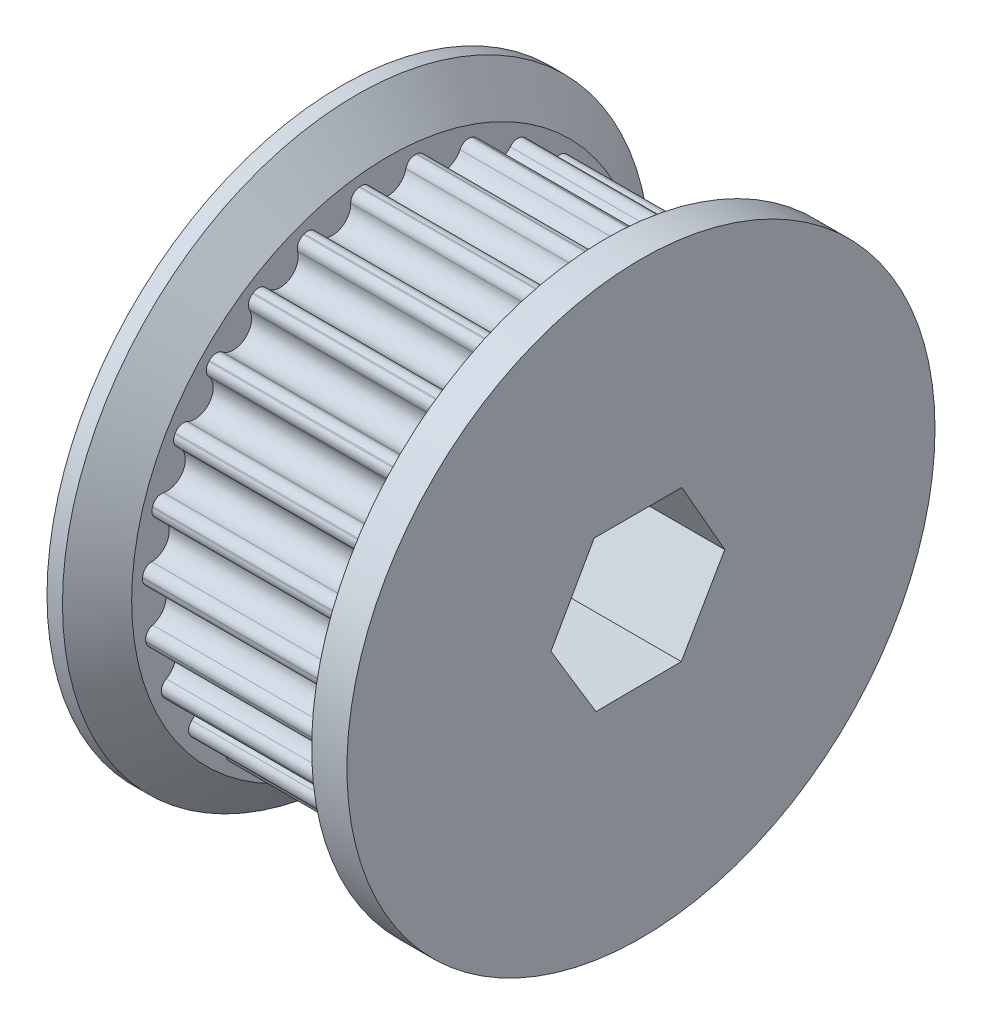
SolidWorks part; units mm, degrees
ref_plane "Front Plane" through (0, 0, 0) normal (0, 0, 1) x (1, 0, 0)
ref_plane "Top Plane" through (0, 0, 0) normal (0, 1, 0) x (1, 0, 0)
ref_plane "Right Plane" through (0, 0, 0) normal (1, 0, 0) x (0, 0, -1)
sketch "Sketch1" plane through (0, 0, 0) normal (1, 0, 0) x (0, 0, -1)
  circle A0 centre (0, 0) radius 20.915
  dimension "D1" = 41.83
extrude "Boss-Extrude1" add sketch "Sketch1" along normal blind 18.5 contours A0
sketch "Sketch8" plane through (18.5, 0, 0) normal (1, 0, 0) x (0, 0, -1)
  line L1 (0, 0) -> (0, 50.3807) construction
  line L7 (-2.5, 21.3391) -> (0, 0) construction
  line L8 (0, 0) -> (2.5, 21.3391) construction
  circle A0 centre (0, 0) radius 21.485 construction
  circle A2 centre (0, 0) radius 20.915 construction
  arc A3 (-1.4883, 20.862) -> (1.4883, 20.862) centre (0, 20.4573) ccw
  arc A6 (-1.4883, 20.862) -> (1.4883, 20.862) centre (0, 0) cw
  point P15 (0, 18.915)
  point P16 (0, 20.915)
  dimension "D4" = 1.5423
  dimension "D2" = 42.97
  dimension "D1" = 5
  dimension "D3" = 2.5
  dimension "D5" = 2
sketch "Sketch9" plane through (0, 0, 0) normal (-1, 0, 0) x (0, 0, 1)
  line L0 (-3.4711, 6.4445) -> (-7.1255, 0.0437)
  line L1 (-7.1255, 0.0437) -> (-3.4298, -6.3571)
  line L2 (-3.4298, -6.3571) -> (3.8268, -6.4097)
  line L3 (3.8268, -6.4097) -> (7.6559, -0.0635)
  line L4 (7.6559, -0.0635) -> (3.9818, 6.4445)
  line L5 (3.9818, 6.4445) -> (-3.4711, 6.4445)
extrude "Cut-Extrude6" cut sketch "Sketch8" against normal blind 43
fillet "Fillet4" radius 0.8 2 edges at (9.25, 20.862, -1.4883) (9.25, 20.862, 1.4883)
sketch "Sketch10" plane through (18.5, 0, 0) normal (1, 0, 0) x (0, 0, -1)
  circle A0 centre (0, 0) radius 25
  dimension "D1" = 50
sketch "Sketch11" plane through (0, 0, 0) normal (-1, 0, 0) x (0, 0, 1)
  circle A0 centre (0, 0) radius 25
  dimension "D1" = 50
pattern_circular "CirPattern1" count 27 over 360 about axis through (0, 0, 0) along (1, 0, 0) of "Cut-Extrude6", "Fillet4"
extrude "Boss-Extrude7" add sketch "Sketch10" along normal blind 3
extrude "Boss-Extrude8" add sketch "Sketch11" along normal blind 4
chamfer "Chamfer1" distance 3.2 angle 40 1 edges at (0, 0, 25)
extrude "Cut-Extrude5" cut sketch "Sketch9" against normal through all both and the other way through all
